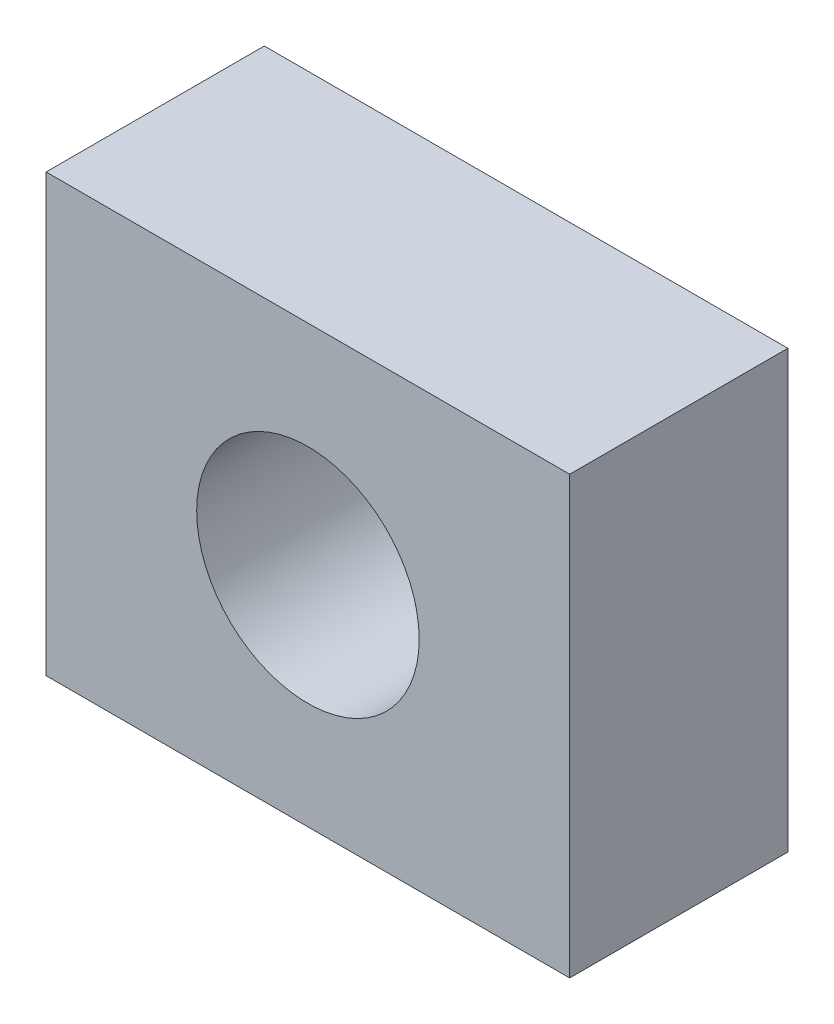
SolidWorks part; units mm, degrees
ref_plane "前基準面" through (0, 0, 0) normal (0, 0, 1) x (1, 0, 0)
ref_plane "上基準面" through (0, 0, 0) normal (0, 1, 0) x (1, 0, 0)
ref_plane "右基準面" through (0, 0, 0) normal (1, 0, 0) x (0, 0, -1)
sketch "草圖1" plane through (0, 0, 0) normal (0, 0, 1) x (1, 0, 0)
  line L1 (-6, 5) -> (6, 5)
  line L2 (-6, 5) -> (-6, -5)
  line L3 (-6, -5) -> (6, -5)
  line L4 (6, 5) -> (6, -5)
  line L5 (-6, 5) -> (6, -5) construction
  line L6 (-6, -5) -> (6, 5) construction
  circle A0 centre (0, 0) radius 2.55
  point P0 (0, 0)
  dimension "D3" = 5.1
  dimension "D1" = 12
  dimension "D2" = 10
extrude "填料-伸長1" add sketch "草圖1" along normal blind 5
